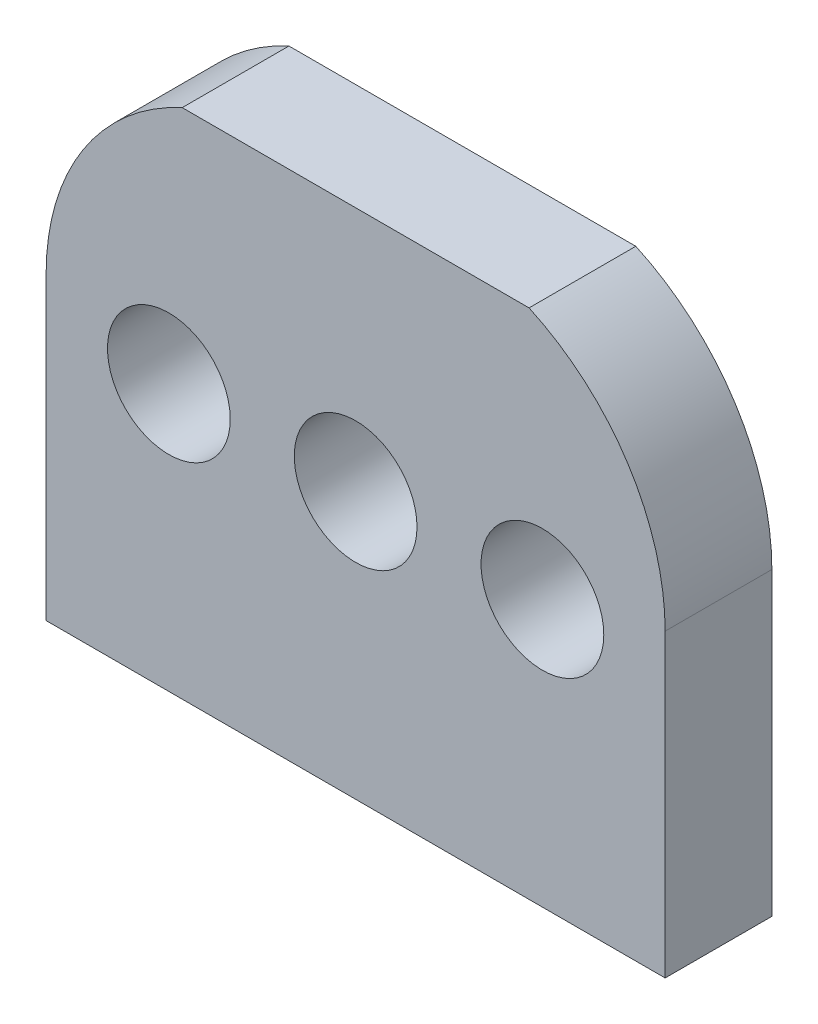
SolidWorks part; units mm, degrees
ref_plane "Płaszczyzna przednia" through (0, 0, 0) normal (0, 0, 1) x (1, 0, 0)
ref_plane "Płaszczyzna górna" through (0, 0, 0) normal (0, 1, 0) x (1, 0, 0)
ref_plane "Płaszczyzna prawa" through (0, 0, 0) normal (1, 0, 0) x (0, 0, -1)
sketch "Szkic1" plane through (0, 0, 0) normal (0, 0, 1) x (1, 0, 0)
  line L0 (-5.8, -4.9941) -> (5.8, -4.9941)
  line L1 (5.8, -4.9941) -> (5.8, 0.6349)
  line L2 (3.25, 4.6059) -> (-3.25, 4.6059)
  line L3 (-5.8, 0.6349) -> (-5.8, -4.9941)
  line L4 (0, -22.1425) -> (0, 47.2243) construction
  arc A0 (5.8, 0.6349) -> (3.25, 4.6059) centre (1.4331, 0.6349) ccw
  arc A1 (-3.25, 4.6059) -> (-5.8, 0.6349) centre (-1.4331, 0.6349) ccw
  circle A2 centre (0, 0) radius 1.15
  circle A3 centre (3.5, 0) radius 1.15
  circle A4 centre (-3.5, 0) radius 1.15
  point P8 (0, -4.9941)
  dimension "D4" = 2.3
  dimension "D6" = 3.5
  dimension "D1" = 6.5
  dimension "D2" = 9.6
  dimension "D3" = 11.6
  dimension "D5" = 3.5
extrude "Dodanie-wyciągnięcie1" add sketch "Szkic1" along normal blind 2
